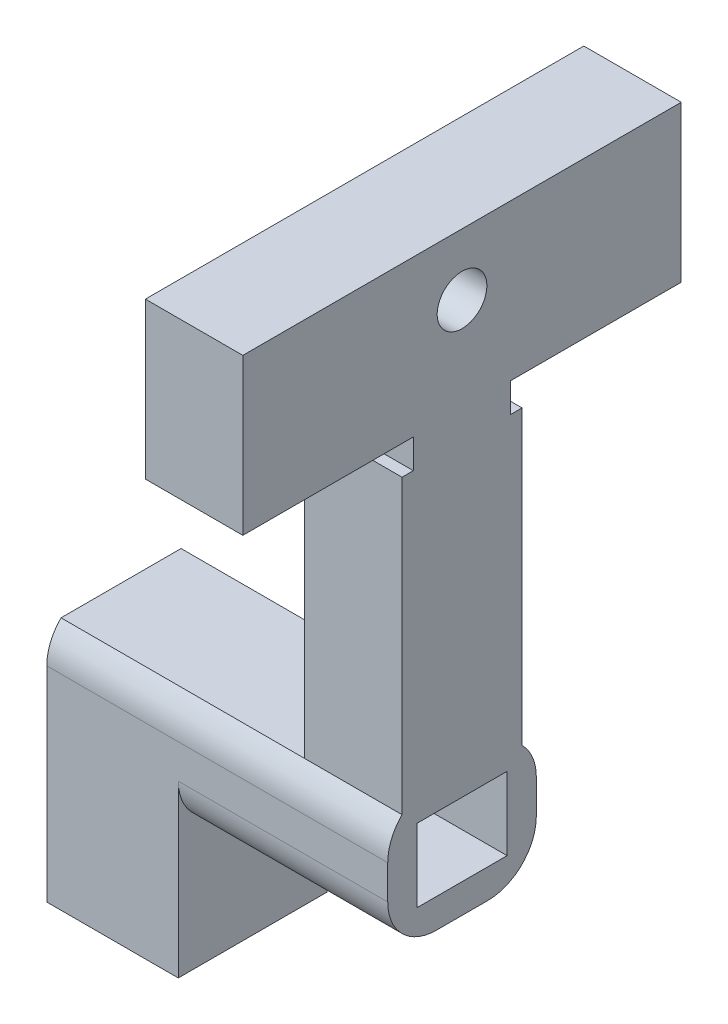
SolidWorks part; units mm, degrees
material "ABS"
ref_plane "Front Plane" through (0, 0, 0) normal (1, 0, 0) x (0, 1, 0)
ref_plane "Top Plane" through (0, 0, 0) normal (0, 0, 1) x (0, 1, 0)
ref_plane "Right Plane" through (0, 0, 0) normal (0, 1, 0) x (-1, 0, 0)
sketch "Sketch1" plane through (0, 0, 0) normal (1, 0, 0) x (0, 1, 0)
  line L0 (13.5, 5.25) -> (13.5, -5.25)
  line L1 (7.5, 9.25) -> (-7.5, 9.25)
  line L2 (7.5, 9.25) -> (7.5, -9.25)
  line L3 (7.5, -9.25) -> (-7.5, -9.25)
  line L4 (-7.5, 9.25) -> (-7.5, -9.25)
  line L5 (7.5, 9.25) -> (-7.5, -9.25) construction
  line L6 (7.5, -9.25) -> (-7.5, 9.25) construction
  line L7 (3.5, -15.25) -> (-3.5, -15.25)
  line L8 (-13.5, 5.25) -> (-13.5, -5.25)
  line L9 (3.5, 15.25) -> (-3.5, 15.25)
  line L10 (-13.5, 15.25) -> (-13.5, -15.25) construction
  line L11 (13.5, 15.25) -> (-13.5, 15.25) construction
  line L12 (13.5, -15.25) -> (-13.5, -15.25) construction
  line L13 (13.5, 15.25) -> (13.5, -15.25) construction
  arc A0 (-13.5, 5.25) -> (-3.5, 15.25) centre (-3.5, 5.25) cw
  arc A1 (-3.5, -15.25) -> (-13.5, -5.25) centre (-3.5, -5.25) cw
  arc A2 (13.5, -5.25) -> (3.5, -15.25) centre (3.5, -5.25) cw
  arc A3 (13.5, 5.25) -> (3.5, 15.25) centre (3.5, 5.25) ccw
  point P0 (0, 0)
  dimension "D4" = 10
  dimension "D1" = 18.5
  dimension "D2" = 15
  dimension "D3" = 6
extrude "Boss-Extrude1" add sketch "Sketch1" along normal mid plane 20 contours L0 A3 L9 A0 L8 A1 L7 A2 L4 L1 L2 L3
sketch "Sketch3" plane through (10, 0, 0) normal (1, 0, 0) x (0, 1, 0)
  line L1 (10.5711, 12.3211) -> (70.5711, 12.3211)
  line L2 (10.5711, 12.3211) -> (10.5711, -12.3211)
  line L3 (10.5711, -12.3211) -> (70.5711, -12.3211)
  line L4 (70.5711, 12.3211) -> (70.5711, -12.3211)
  arc A0 (13.5, 5.25) -> (3.5, 15.25) centre (3.5, 5.25) ccw construction
  arc A1 (3.5, -15.25) -> (13.5, -5.25) centre (3.5, -5.25) ccw construction
  point P10 (10.5711, -12.3211)
  dimension "D1" = 60
extrude "Boss-Extrude2" add sketch "Sketch3" against normal blind 20
sketch "Sketch4" plane through (10, 0, 0) normal (1, 0, 0) x (0, 1, 0)
  line L0 (70.5711, -12.3211) -> (70.5711, 12.3211) construction
  line L1 (70.5711, 10) -> (76.5711, 10)
  line L2 (70.5711, 10) -> (70.5711, -10)
  line L3 (70.5711, -10) -> (76.5711, -10)
  line L5 (76.5711, -10) -> (76.5711, -45)
  line L6 (76.5711, 45) -> (108.5711, 45)
  line L7 (76.5711, 45) -> (76.5711, 10)
  line L8 (76.5711, -45) -> (108.5711, -45)
  line L9 (108.5711, 45) -> (108.5711, -45)
  line L10 (7.5, 9.25) -> (7.5, -9.25) construction
  point P12 (7.5, 0)
  point P13 (70.5711, 0)
  point P14 (108.5711, 0)
  dimension "D1" = 20
  dimension "D2" = 90
  dimension "D3" = 6
  dimension "D4" = 32
extrude "Boss-Extrude3" add sketch "Sketch4" against normal up to surface (20 mm away)
sketch "Sketch5" plane through (10, 0, 0) normal (1, 0, 0) x (0, 1, 0)
  circle A0 centre (95.9211, 0) radius 5.1
  dimension "D1" = 10.2
  dimension "D2" = 25.35
extrude "Cut-Extrude1" cut sketch "Sketch5" against normal through all
sketch "Sketch6" plane through (-10, 0, 0) normal (-1, 0, 0) x (0, -1, 0)
  line L0 (-10.5711, 12.3211) -> (-10.5711, -12.3211)
  line L2 (-7.5, 9.25) -> (7.5, 9.25)
  line L3 (-7.5, 9.25) -> (-7.5, -9.25)
  line L4 (-7.5, -9.25) -> (7.5, -9.25)
  line L5 (7.5, 9.25) -> (7.5, -9.25)
  line L14 (-70.5711, -12.3211) -> (-10.5711, -12.3211)
  line L15 (-3.5, -15.25) -> (3.5, -15.25)
  line L16 (13.5, -5.25) -> (13.5, 5.25)
  line L17 (3.5, 15.25) -> (-3.5, 15.25)
  line L18 (-10.5711, 12.3211) -> (-70.5711, 12.3211)
  line L19 (-70.5711, 12.3211) -> (-70.5711, 10)
  line L20 (-70.5711, 10) -> (-76.5711, 10)
  line L21 (-76.5711, 10) -> (-76.5711, 45)
  line L22 (-76.5711, 45) -> (-108.5711, 45)
  line L23 (-108.5711, 45) -> (-108.5711, -45)
  line L24 (-108.5711, -45) -> (-76.5711, -45)
  line L25 (-76.5711, -45) -> (-76.5711, -10)
  line L26 (-76.5711, -10) -> (-70.5711, -10)
  line L27 (-70.5711, -10) -> (-70.5711, -12.3211)
  line L29 (-3.5, -15.25) -> (3.5, -15.25)
  line L30 (13.5, -5.25) -> (13.5, 5.25)
  line L31 (3.5, 15.25) -> (-3.5, 15.25)
  arc A4 (-10.5711, -12.3211) -> (-3.5, -15.25) centre (-3.5, -5.25) ccw
  arc A5 (3.5, -15.25) -> (13.5, -5.25) centre (3.5, -5.25) ccw
  arc A6 (13.5, 5.25) -> (3.5, 15.25) centre (3.5, 5.25) ccw
  arc A7 (-3.5, 15.25) -> (-10.5711, 12.3211) centre (-3.5, 5.25) ccw
  arc A8 (-10.5711, -12.3211) -> (-3.5, -15.25) centre (-3.5, -5.25) ccw
  arc A9 (3.5, -15.25) -> (13.5, -5.25) centre (3.5, -5.25) ccw
  arc A10 (13.5, 5.25) -> (3.5, 15.25) centre (3.5, 5.25) ccw
  arc A11 (-3.5, 15.25) -> (-10.5711, 12.3211) centre (-3.5, 5.25) ccw
  dimension "D1" = 0
extrude "Boss-Extrude4" add sketch "Sketch6" along normal blind 50
sketch "Sketch7" plane through (-60, 0, 0) normal (-1, 0, 0) x (0, -1, 0)
  line L0 (13.5, -5.25) -> (13.5, 5.25) construction
  line L1 (3.5, 15.25) -> (13.5, 15.25)
  line L2 (3.5, 15.25) -> (3.5, 9.25)
  line L3 (3.5, -15.25) -> (13.5, -15.25)
  line L4 (13.5, 15.25) -> (13.5, -15.25)
  line L5 (-7.5, -9.25) -> (7.5, -9.25) construction
  line L6 (7.5, -9.25) -> (7.5, 9.25) construction
  line L7 (7.5, -4.8072) -> (7.5, 7.3) construction
  line L8 (7.5, 9.25) -> (-7.5, 9.25) construction
  line L9 (3.5, -9.25) -> (7.5, -9.25)
  line L10 (7.5, -9.25) -> (7.5, 9.25)
  line L11 (7.5, -4.8072) -> (7.5, 7.3)
  line L12 (7.5, 9.25) -> (3.5, 9.25)
  line L13 (3.5, -9.25) -> (3.5, -15.25)
  point P5 (3.5, -15.25)
extrude "Boss-Extrude5" add sketch "Sketch7" against normal blind 25 contours L1 L4 L3 L13 L9 L10 L12 L2
sketch "Sketch8" plane through (0, -13.5, 0) normal (0, -1, 0) x (1, 0, 0)
  line L0 (-35, -15.25) -> (-60, -15.25) construction
  line L1 (-60, 15.25) -> (-57, 15.25)
  line L2 (-60, 15.25) -> (-60, -15.25)
  line L3 (-60, -15.25) -> (-57, -15.25)
  line L4 (-57, 15.25) -> (-57, -15.25)
  dimension "D1" = 3
extrude "Boss-Extrude6" add sketch "Sketch8" along normal blind 25
sketch "Sketch9" plane through (-57, 0, 0) normal (1, 0, 0) x (0, 1, 0)
  line L0 (-13.5, 15.25) -> (-13.5, 5.25) construction
  line L1 (-38.5, 15.25) -> (-13.5, 15.25)
  line L2 (-38.5, 15.25) -> (-38.5, 13.75)
  line L3 (-38.5, 13.75) -> (-13.5, 13.75)
  line L4 (-13.5, 15.25) -> (-13.5, 13.75)
  line L5 (-13.5, -15.25) -> (-13.5, 15.25) construction
  line L6 (-38.5, -15.25) -> (-13.5, -15.25)
  line L7 (-38.5, -15.25) -> (-38.5, -13.75)
  line L8 (-38.5, -13.75) -> (-13.5, -13.75)
  line L9 (-13.5, -15.25) -> (-13.5, -13.75)
  dimension "D1" = 1.5
  dimension "D2" = 1.5
extrude "Boss-Extrude7" add sketch "Sketch9" along normal up to vertex
sketch "Sketch10" plane through (-35, 0, 0) normal (1, 0, 0) x (0, 1, 0)
  line L2 (-38.5, 15.25) -> (-38.5, -15.25)
  line L6 (-13.5, 5.25) -> (-13.5, -5.25)
  line L10 (-3.5, 15.25) -> (-38.5, 15.25)
  line L11 (-38.5, 15.25) -> (-38.5, 13.75)
  line L12 (-38.5, 13.75) -> (-13.5, 13.75)
  line L13 (-13.5, 13.75) -> (-13.5, 5.25)
  line L14 (-3.5, 15.25) -> (-38.5, 15.25)
  line L15 (-38.5, 15.25) -> (-38.5, -15.25)
  line L18 (-38.5, -15.25) -> (-3.5, -15.25)
  line L19 (-13.5, -5.25) -> (-13.5, -13.75)
  line L20 (-13.5, -13.75) -> (-38.5, -13.75)
  line L21 (-38.5, -13.75) -> (-38.5, -15.25)
  line L22 (-38.5, -15.25) -> (-3.5, -15.25)
  arc A1 (-3.5, 15.25) -> (-13.5, 5.25) centre (-3.5, 5.25) ccw
  arc A2 (-3.5, 15.25) -> (-13.5, 5.25) centre (-3.5, 5.25) ccw
  arc A3 (-13.5, -5.25) -> (-3.5, -15.25) centre (-3.5, -5.25) ccw
  arc A4 (-13.5, -5.25) -> (-3.5, -15.25) centre (-3.5, -5.25) ccw
  point P7 (-38.5, -15.5028)
  line M5 (-3.5, 15.25) -> (-38.5, 15.25)
  line M6 (-38.5, 15.25) -> (-38.5, 13.75)
  line M7 (-38.5, 13.75) -> (-13.5, 13.75)
  line M8 (-13.5, 13.75) -> (-13.5, 5.25)
  arc M9 (-13.5, 5.25) -> (-3.5, 15.25) centre (-3.5, 5.25) cw
  dimension "D1" = 0
  dimension "D2" = 0
extrude "Boss-Extrude11" add sketch "Sketch10" along normal blind 2 contours A4 L6 L2 L22 M8 M7 | M9 M5 M6 M7 M8
